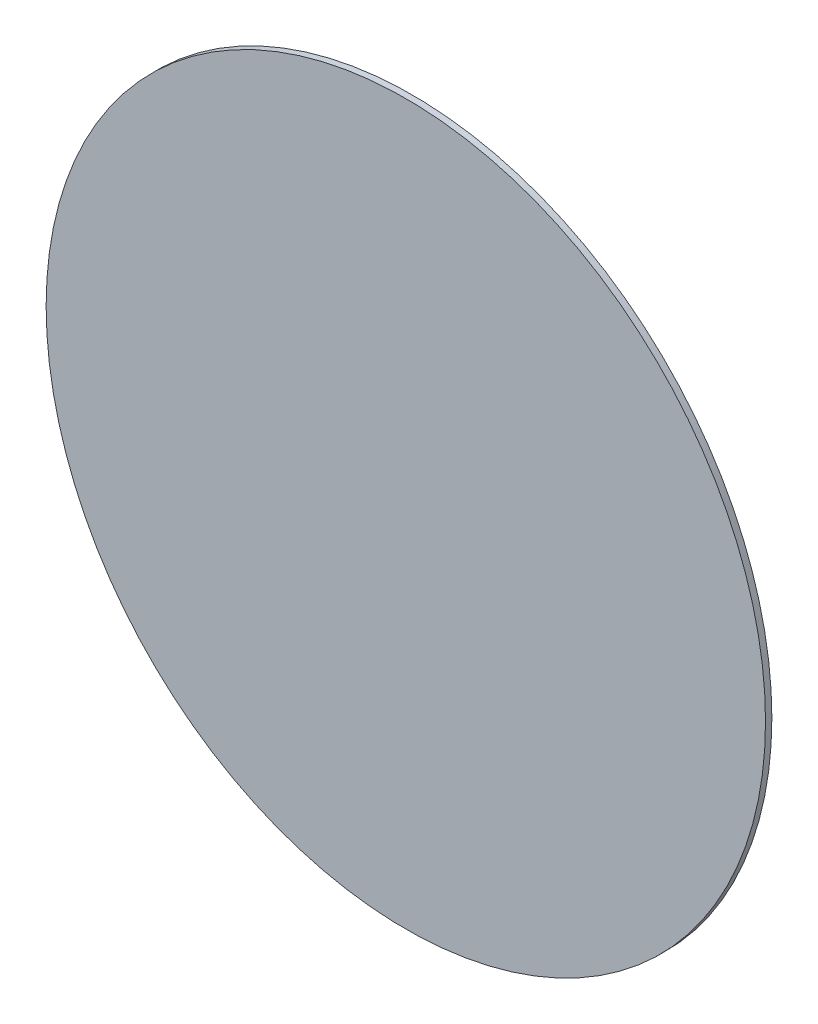
SolidWorks part; units mm, degrees
ref_plane "Front Plane" through (0, 0, 0) normal (0, 0, 1) x (1, 0, 0)
ref_plane "Top Plane" through (0, 0, 0) normal (0, 1, 0) x (1, 0, 0)
ref_plane "Right Plane" through (0, 0, 0) normal (1, 0, 0) x (0, 0, -1)
sketch "Sketch1" plane through (0, 0, 0) normal (0, 0, 1) x (1, 0, 0)
  circle A0 centre (-74.4149, -31.3834) radius 113.3367
extrude "Boss-Extrude1" add sketch "Sketch1" along normal blind 2
